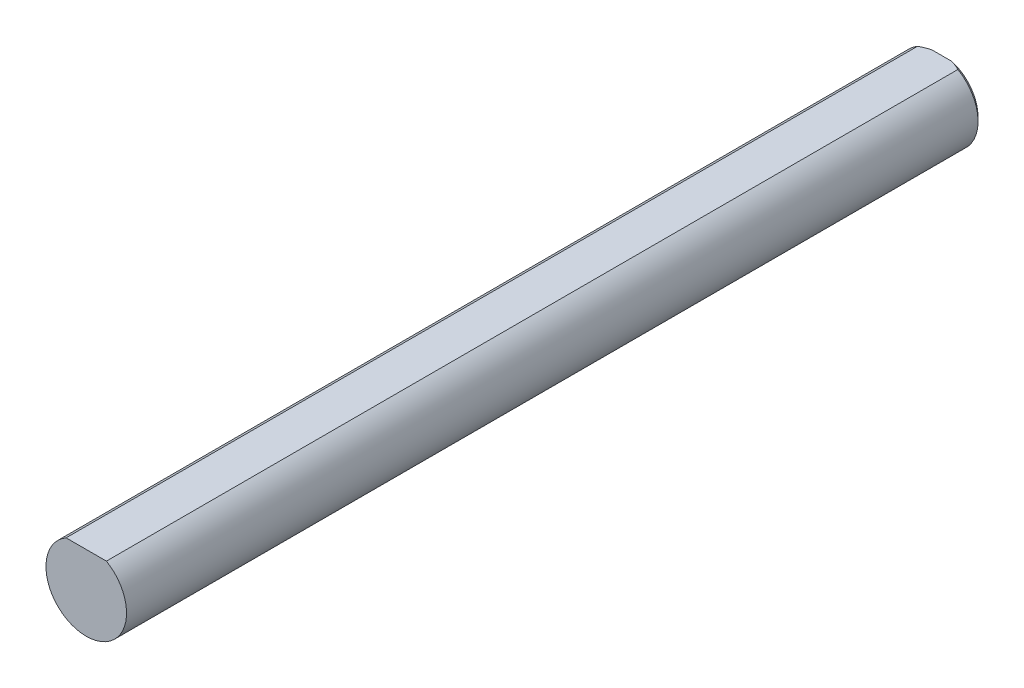
SolidWorks part; units mm, degrees
ref_plane "Front Plane" through (0, 0, 0) normal (0, 0, 1) x (1, 0, 0)
ref_plane "Top Plane" through (0, 0, 0) normal (0, 1, 0) x (1, 0, 0)
ref_plane "Right Plane" through (0, 0, 0) normal (1, 0, 0) x (0, 0, -1)
sketch "Sketch1" plane through (0, 0, 0) normal (0, 0, 1) x (1, 0, 0)
  line L0 (-1.5875, 2.7496) -> (1.5875, 2.7496) construction
  circle A1 centre (0, 0) radius 3.175 construction
  dimension "Diameter" = 6.35
  dimension "Flat Width" = 3.175
sketch "Sketch2" plane through (0, 0, 0) normal (1, 0, 0) x (0, 0, -1)
  line L0 (-76.2, 3.175) -> (76.2, 3.175) construction
  line L1 (0, 3.175) -> (0, -3.175) construction
  line L2 (0, 3.175) -> (0, -3.175) construction
  line L3 (-76.2, 3.175) -> (-76.2, -3.175) construction
  line L4 (-76.2, -3.175) -> (76.2, -3.175) construction
  point P2 (0, 3.175)
  point P3 (63.5, 3.175)
  point P4 (-63.5, 3.175)
  dimension "Length" = 152.4
  dimension "D2" = 12.7
  dimension "D1" = 12.7
  dimension "D-Profile Length" = 152.4
sketch "Sketch3" plane through (0, 0, 0) normal (0, 0, 1) x (1, 0, 0)
  circle A1 centre (0, 0) radius 3.175 construction
  circle A3 centre (0, 0) radius 3.175
extrude "Boss-Extrude2" add sketch "Sketch3" along normal up to vertex (76.2 mm away) and the other way up to vertex (76.2 mm away) up to point (0, 3.175, 76.2) other way up to point (0, 3.175, -76.2)
sketch "Sketch10" plane through (0, 0, 0) normal (0, 0, 1) x (1, 0, 0)
  line L0 (-1.5875, 2.7496) -> (1.5875, 2.7496)
  line L1 (0, 0) -> (0, 3.175) construction
  circle A0 centre (0, 0) radius 3.175 construction
  circle A1 centre (0, 0) radius 3.175 construction
  arc A2 (-1.5875, 2.7496) -> (1.5875, 2.7496) centre (0, 0) cw
extrude "Cut-Extrude5" cut sketch "Sketch10" against normal through all both and the other way through all
chamfer "Chamfer1" distance 0.3175 angle 45 4 edges at (0, -3.175, 76.2) (0, -3.175, -76.2) (0, 2.7496, -76.2) (0, 2.7496, 76.2)
sketch "Sketch11" plane through (0, 0, 76.2) normal (0, 0, 1) x (1, 0, 0)
  line L1 (-4.7889, -4.1028) -> (4.7889, -4.1028)
  line L2 (-4.7889, -4.1028) -> (-4.7889, 4.1028)
  line L3 (-4.7889, 4.1028) -> (4.7889, 4.1028)
  line L4 (4.7889, -4.1028) -> (4.7889, 4.1028)
  line L5 (-4.7889, -4.1028) -> (4.7889, 4.1028) construction
  line L6 (-4.7889, 4.1028) -> (4.7889, -4.1028) construction
  point P0 (0, 0)
extrude "Cut-Extrude6" cut sketch "Sketch11" against normal blind 85
equation "\"D1@Chamfer1\"= \"Diameter@Sketch1\" / 20"
equation "\"D1@Sketch2\"=\"Diameter@Sketch1\"*2"
equation "\"D2@Sketch2\"=\"D1@Sketch2\""
